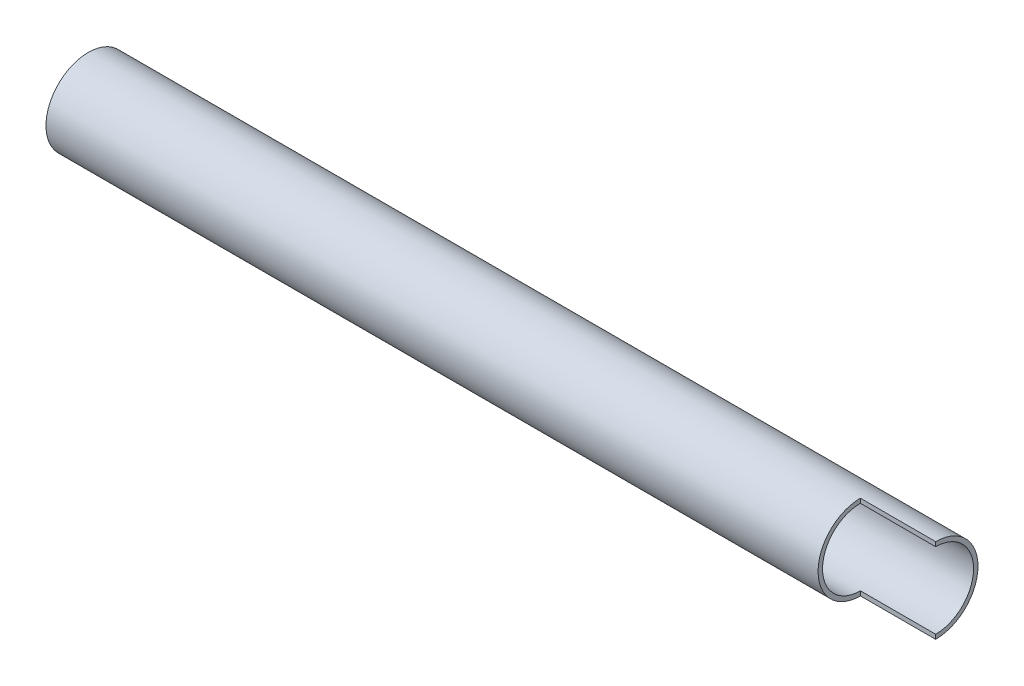
SolidWorks part; units mm, degrees
ref_plane "Front" through (0, 0, 0) normal (0, 0, 1) x (1, 0, 0)
ref_plane "Top" through (0, 0, 0) normal (0, 1, 0) x (1, 0, 0)
ref_plane "Right" through (0, 0, 0) normal (1, 0, 0) x (0, 0, -1)
sketch "Croquis1" plane through (0, 0, 0) normal (1, 0, 0) x (0, 0, -1)
  circle A1 centre (0, 0) radius 57.15
  circle A2 centre (0, 0) radius 51.15
  dimension "D1" = 114.3
  dimension "D2" = 6
extrude "Saliente-Extruir1" add sketch "Croquis1" along normal blind 1144
sketch "Croquis2" plane through (1144, 0, 0) normal (1, 0, 0) x (0, 0, -1)
  line L0 (-48.1402, -30.8) -> (48.1402, -30.8)
  arc A2 (-48.1402, -30.8) -> (48.1402, -30.8) centre (0, 0) ccw
  arc A3 (-40.8373, -30.8) -> (40.8373, -30.8) centre (0, 0) ccw
sketch "Croquis3" plane through (1144, 0, 0) normal (1, 0, 0) x (0, 0, -1)
  line L0 (0, 57.15) -> (0, -57.15)
  arc A0 (0, 57.15) -> (0, -57.15) centre (0, 0) ccw
  arc A1 (0, 51.15) -> (0, -51.15) centre (0, 0) ccw
  circle M1 centre (0, 0) radius 57.15
  circle M2 centre (0, 0) radius 51.15
extrude "Cortar-Extruir1" cut sketch "Croquis3" against normal blind 101.6 contours L0 M1 M2
